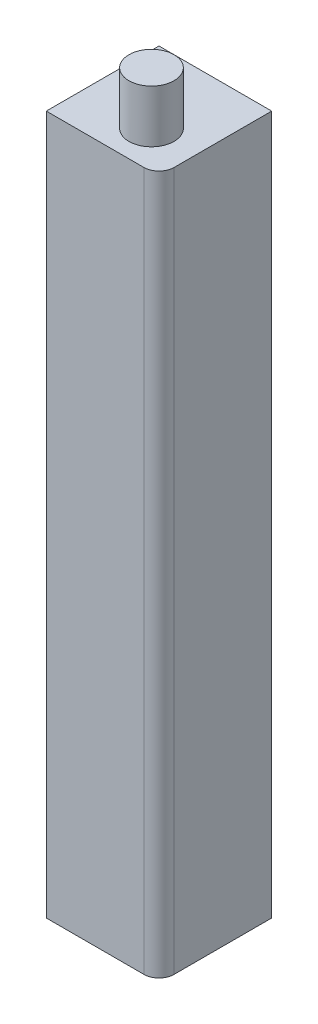
SolidWorks part; units mm, degrees
ref_plane "Front Plane" through (0, 0, 0) normal (0, 0, 1) x (1, 0, 0)
ref_plane "Top Plane" through (0, 0, 0) normal (0, 1, 0) x (1, 0, 0)
ref_plane "Right Plane" through (0, 0, 0) normal (1, 0, 0) x (0, 0, -1)
sketch "Sketch1" plane through (0, 0, 0) normal (0, 1, 0) x (1, 0, 0)
  line L0 (-68.486, 0) -> (57.6746, 0) construction
  line L1 (0, 62.7099) -> (0, -58.019) construction
  line L3 (-7.5, -7.5) -> (7.5, -7.5)
  line L4 (-7.5, -7.5) -> (-7.5, 7.5)
  line L5 (-7.5, 7.5) -> (7.5, 7.5)
  line L6 (7.5, -7.5) -> (7.5, 7.5)
  line L7 (-7.5, -7.5) -> (7.5, 7.5) construction
  line L8 (-7.5, 7.5) -> (7.5, -7.5) construction
  point P5 (0, 0)
  dimension "D1" = 15
  dimension "D2" = 15
extrude "Boss-Extrude1" add sketch "Sketch1" along normal blind 93
sketch "Sketch2" plane through (0, 93, 0) normal (0, 1, 0) x (1, 0, 0)
  line L0 (7.5, -7.5) -> (7.5, 7.5) construction
  line L1 (-7.5, -7.5) -> (7.5, -7.5) construction
  circle A0 centre (1.5, -2.5) radius 3
  dimension "D1" = 6
  dimension "D2" = 6
  dimension "D3" = 5
extrude "Boss-Extrude2" add sketch "Sketch2" along normal blind 7
fillet "Fillet1" radius 2 1 edges at (7.5, 46.5, 7.5)
